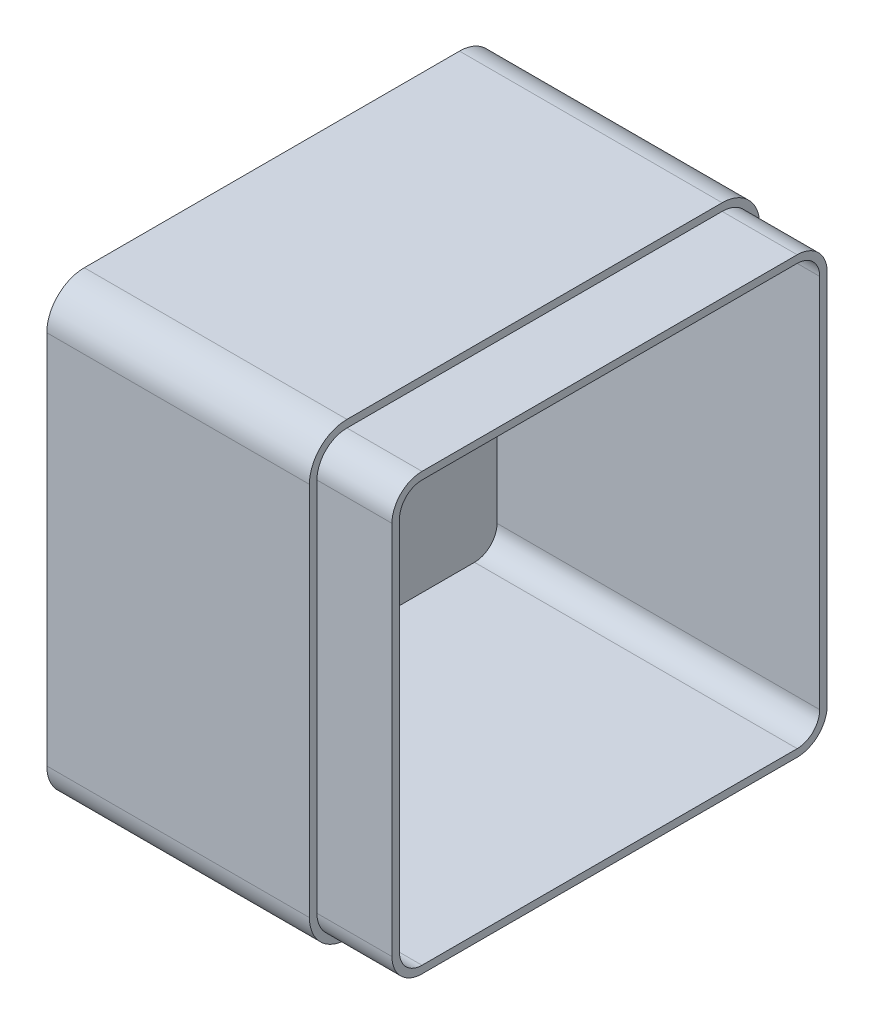
SolidWorks part; units mm, degrees
ref_plane "Ebene vorne" through (0, 0, 0) normal (1, 0, 0) x (0, 1, 0)
ref_plane "Ebene oben" through (0, 0, 0) normal (0, 0, 1) x (0, 1, 0)
ref_plane "Ebene rechts" through (0, 0, 0) normal (0, 1, 0) x (-1, 0, 0)
sketch "Skizze1" plane through (0, 0, 0) normal (1, 0, 0) x (0, 1, 0)
  line L1 (0, 0) -> (120, 0)
  line L2 (0, 0) -> (0, 120)
  line L3 (0, 120) -> (120, 120)
  line L4 (120, 0) -> (120, 120)
  dimension "D1" = 120
  dimension "D2" = 120
extrude "Aufsatz-Linear austragen1" add sketch "Skizze1" along normal blind 90
fillet "Verrundung1" radius 10 4 edges at (45, 120, 0) (45, 0, 0) (45, 0, 120) (45, 120, 120)
shell "Wandung1" thickness 4
sketch "Skizze2" plane through (90, 0, 0) normal (1, 0, 0) x (0, 1, 0)
  line L0 (10, 2) -> (110, 2)
  line L1 (118, 10) -> (118, 110)
  line L2 (110, 118) -> (10, 118)
  line L3 (2, 110) -> (2, 10)
  line L4 (10, 0) -> (110, 0)
  line L5 (120, 10) -> (120, 110)
  line L6 (110, 120) -> (10, 120)
  line L7 (0, 110) -> (0, 10)
  line L8 (10, 0) -> (110, 0)
  line L9 (120, 10) -> (120, 110)
  line L10 (110, 120) -> (10, 120)
  line L11 (0, 110) -> (0, 10)
  arc A0 (110, 2) -> (118, 10) centre (110, 10) ccw
  arc A1 (118, 110) -> (110, 118) centre (110, 110) ccw
  arc A2 (10, 118) -> (2, 110) centre (10, 110) ccw
  arc A3 (2, 10) -> (10, 2) centre (10, 10) ccw
  arc A4 (110, 0) -> (120, 10) centre (110, 10) ccw
  arc A5 (120, 110) -> (110, 120) centre (110, 110) ccw
  arc A6 (10, 120) -> (0, 110) centre (10, 110) ccw
  arc A7 (0, 10) -> (10, 0) centre (10, 10) ccw
  arc A8 (110, 0) -> (120, 10) centre (110, 10) ccw
  arc A9 (120, 110) -> (110, 120) centre (110, 110) ccw
  arc A10 (10, 120) -> (0, 110) centre (10, 110) ccw
  arc A11 (0, 10) -> (10, 0) centre (10, 10) ccw
  dimension "D1" = 0
  dimension "D2" = 2
extrude "Schnitt-Linear austragen1" cut sketch "Skizze2" against normal blind 20
